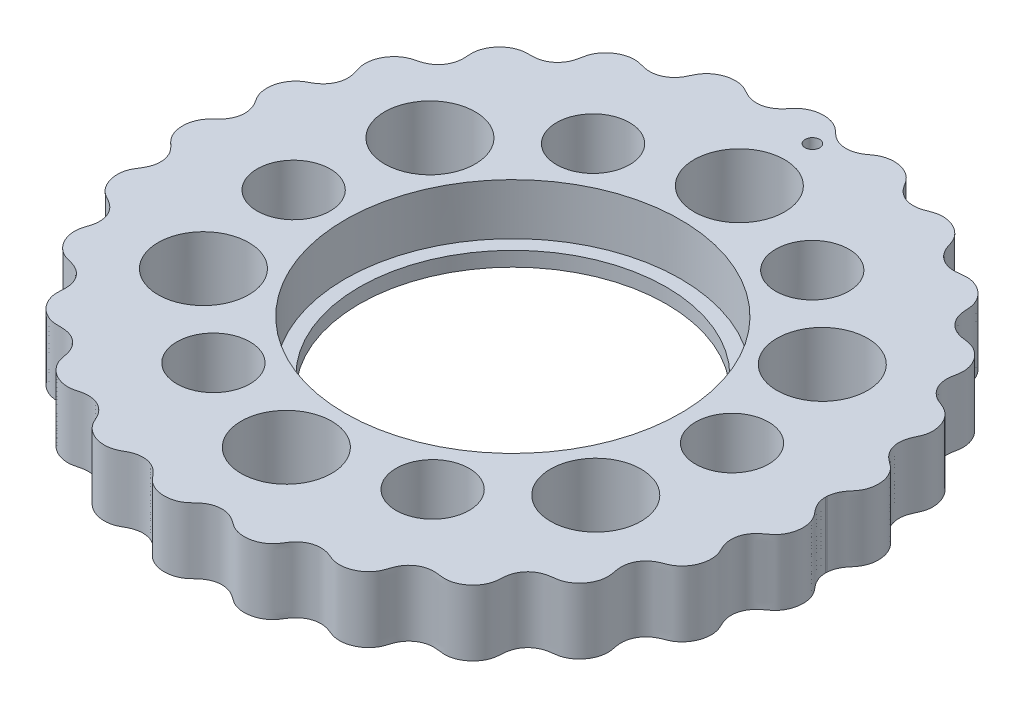
SolidWorks part; units mm, degrees
material "Like ABS"
ref_plane "Front Plane" through (0, 0, 0) normal (0, 0, 1) x (1, 0, 0)
ref_plane "Top Plane" through (0, 0, 0) normal (0, 1, 0) x (1, 0, 0)
ref_plane "Right Plane" through (0, 0, 0) normal (1, 0, 0) x (0, 0, -1)
sketch "Sketch1" plane through (0, 0, 0) normal (0, 1, 0) x (1, 0, 0)
  spline S0 degree 4 poles (18.6418, 10.5579) (18.7303, 10.3073) (18.9166, 10.0009) (19.2494, 9.7061) (19.7196, 9.4909) (20.0347, 9.3822) (20.3607, 9.2005) (20.6669, 8.9259) (20.9237, 8.5637) (21.1025, 8.1229) (21.1716, 7.6934) (21.1505, 7.3003) (21.0688, 6.9931) (20.9708, 6.7724) (20.8656, 6.5558) (20.7571, 6.3016) (20.668, 5.9591) (20.6615, 5.5306) (20.7798, 5.0848) (20.995, 4.7201) (21.2612, 4.4411) (21.5433, 4.2347) (21.8022, 4.0525) (22.045, 3.7986) (22.2501, 3.4744) (22.3932, 3.088) (22.4554, 2.6541) (22.4292, 2.264) (22.3433, 1.9326) (22.2197, 1.6594) (22.0797, 1.4428) (21.916, 1.2513) (21.7597, 1.0607) (21.6432, 0.8829) (21.5614, 0.7256) (21.5052, 0.5887) (21.4677, 0.4773) (21.4407, 0.371) (21.4222, 0.2789) (21.4076, 0.1762) (21.3996, 0.0464) (21.3987, -0.0271) (21.4069, -0.1732) (21.4219, -0.2777) (21.4443, -0.389) (21.474, -0.4968) (21.5197, -0.6294) (21.5968, -0.8019) (21.7184, -1.008) (21.898, -1.2319) (22.1006, -1.4645) (22.2832, -1.769) (22.4134, -2.1479) (22.4617, -2.5888) (22.4015, -3.0697) (22.2467, -3.4857) (22.0281, -3.8227) (21.7701, -4.0798) (21.5014, -4.2617) (21.2219, -4.4765) (20.9658, -4.7612) (20.7673, -5.1214) (20.6622, -5.5479) (20.6698, -5.9517) (20.758, -6.3091) (20.8905, -6.614) (21.0265, -6.8799) (21.1366, -7.2172) (21.1778, -7.6258) (21.1184, -8.0782) (20.9356, -8.544) (20.6762, -8.9143) (20.3782, -9.1865) (20.0975, -9.3492) (19.8699, -9.4384) (19.6428, -9.5272) (19.3961, -9.6431) (19.1116, -9.8349) (18.832, -10.1379) (18.628, -10.5267) (18.5387, -10.9199) (18.5379, -11.2864) (18.592, -11.6131) (18.6566, -11.9035) (18.677, -12.2563) (18.6137, -12.6603) (18.4454, -13.0751) (18.1627, -13.4684) (17.8328, -13.7578) (17.5261, -13.9295) (17.2611, -14.0207) (17.0556, -14.0631) (16.8894, -14.0847) (16.6814, -14.109) (16.4045, -14.1586) (16.0694, -14.2753) (15.709, -14.5087) (15.4048, -14.8538) (15.22, -15.2365) (15.1451, -15.5766) (15.1235, -15.8472) (15.1117, -16.0828) (15.086, -16.318) (15.0048, -16.6177) (14.8327, -16.9608) (14.5728, -17.2882) (14.2228, -17.573) (13.8443, -17.7633) (13.4619, -17.8627) (13.1375, -17.8769) (12.8864, -17.8466) (12.6365, -17.8129) (12.3547, -17.7936) (11.9999, -17.826) (11.5933, -17.9665) (11.2155, -18.2286) (10.9449, -18.555) (10.7906, -18.8655) (10.7038, -19.1216) (10.6339, -19.346) (10.5494, -19.5661) (10.3954, -19.8343) (10.1432, -20.1216) (9.8068, -20.3748) (9.389, -20.5646) (8.9692, -20.6515) (8.5724, -20.6465) (8.2199, -20.567) (7.923, -20.4379) (7.5842, -20.3142) (7.1893, -20.2495) (6.7562, -20.2849) (6.3193, -20.4504) (5.9761, -20.7038) (5.7522, -20.9667) (5.6061, -21.1928) (5.4827, -21.3919) (5.3455, -21.5826) (5.1293, -21.8019) (4.8139, -22.0153) (4.4253, -22.1753) (3.9731, -22.254) (3.5443, -22.2322) (3.1598, -22.1268) (2.8746, -21.9781) (2.6779, -21.8341) (2.4816, -21.6903) (2.2448, -21.5396) (1.9136, -21.3968) (1.4802, -21.3269) (1.0089, -21.3849) (0.6139, -21.5536) (0.3043, -21.7789) (0.0638, -22.0167) (-0.1578, -22.2142) (-0.448, -22.3889) (-0.804, -22.5195) (-1.2236, -22.5798) (-1.6888, -22.543) (-2.103, -22.4123) (-2.4495, -22.2124) (-2.7192, -21.9674) (-2.917, -21.7081) (-3.1594, -21.4371) (-3.4804, -21.1931) (-3.8955, -21.0162) (-4.3266, -20.9688) (-4.6986, -21.0199) (-5.0064, -21.124) (-5.2473, -21.2408) (-5.4821, -21.381) (-5.7377, -21.4982) (-6.0485, -21.5812) (-6.4098, -21.6099) (-6.8181, -21.5611) (-7.2514, -21.4098) (-7.6166, -21.1808) (-7.9026, -20.8985) (-8.1015, -20.5918) (-8.2285, -20.29) (-8.3985, -19.9669) (-8.652, -19.6514) (-9.0131, -19.3798) (-9.4202, -19.2304) (-9.7928, -19.1908) (-10.1152, -19.2172) (-10.3762, -19.2717) (-10.6376, -19.3487) (-10.9137, -19.3967) (-11.2341, -19.3981) (-11.5896, -19.3347) (-11.9717, -19.185) (-12.3532, -18.9296) (-12.6493, -18.6154) (-12.8557, -18.2686) (-12.9701, -17.92) (-13.0178, -17.5947) (-13.1323, -17.1226) (-13.3987, -16.6511) (-13.8075, -16.3174) (-14.2713, -16.1489) (-14.5895, -16.0966) (-14.8545, -16.0861) (-15.1259, -16.0953) (-15.4042, -16.0714) (-15.7134, -15.9919) (-16.04, -15.8412) (-16.3715, -15.6006) (-16.6766, -15.2574) (-16.8844, -14.8781) (-16.9969, -14.4887) (-17.0187, -14.1212) (-16.9833, -13.793) (-16.9797, -13.3053) (-17.125, -12.7827) (-17.4421, -12.3604) (-17.8514, -12.0856) (-18.1462, -11.9584) (-18.3995, -11.8839) (-18.6637, -11.8253) (-18.9258, -11.7315) (-19.2037, -11.5768) (-19.4806, -11.3493) (-19.7404, -11.0335) (-19.9495, -10.6246) (-20.0552, -10.2044) (-20.0656, -9.7977) (-19.9928, -9.4353) (-19.8758, -9.1255) (-19.784, -8.7675) (-19.7615, -8.359) (-19.8515, -7.9142) (-20.0565, -7.5324) (-20.3067, -7.2568) (-20.5604, -7.063) (-20.7872, -6.9295) (-21.0274, -6.8071) (-21.2562, -6.6501) (-21.4849, -6.4308) (-21.6945, -6.1418) (-21.8663, -5.7714) (-21.9656, -5.3231) (-21.9623, -4.8888) (-21.8783, -4.5321) (-21.7613, -4.2706) (-21.6335, -4.0565) (-21.4949, -3.8496) (-21.3375, -3.5602) (-21.217, -3.1677) (-21.1974, -2.7137) (-21.3049, -2.294) (-21.4811, -1.967) (-21.6794, -1.7187) (-21.866, -1.5347) (-22.0671, -1.3567) (-22.2478, -1.1472) (-22.4129, -0.878) (-22.5421, -0.5466) (-22.6173, -0.1335) (-22.5959, 0.3506) (-22.4661, 0.7918) (-22.2676, 1.1298) (-22.0677, 1.351) (-21.9165, 1.4911) (-21.796, 1.6037) (-21.6524, 1.752) (-21.4809, 1.9683) (-21.3145, 2.273) (-21.2055, 2.6829) (-21.2106, 3.1412) (-21.3262, 3.5408) (-21.5033, 3.8665) (-21.6848, 4.132) (-21.8148, 4.3747) (-21.9183, 4.6798) (-21.9709, 5.0457) (-21.9452, 5.4724) (-21.8071, 5.9373) (-21.6001, 6.2936) (-21.3746, 6.5445) (-21.1778, 6.703) (-21.036, 6.7965) (-20.8505, 6.8989) (-20.6264, 7.0191) (-20.3573, 7.2062) (-20.0813, 7.4975) (-19.8657, 7.8826) (-19.7711, 8.2901) (-19.7742, 8.6526) (-19.8318, 8.9622) (-19.9084, 9.2105) (-19.997, 9.4621) (-20.0507, 9.7317) (-20.0625, 10.045) (-20.0135, 10.3947) (-19.8723, 10.8081) (-19.6342, 11.1845) (-19.3432, 11.4777) (-19.047, 11.6699) (-18.8186, 11.7726) (-18.6046, 11.837) (-18.4132, 11.8827) (-18.176, 11.9484) (-17.9009, 12.0583) (-17.5928, 12.2516) (-17.2948, 12.562) (-17.0941, 12.9283) (-16.9937, 13.3178) (-16.9784, 13.6461) (-16.9965, 13.9004) (-17.0099, 14.1124) (-17.0076, 14.2827) (-16.9801, 14.5346) (-16.8899, 14.8605) (-16.7006, 15.227) (-16.3828, 15.5933) (-16.0373, 15.8442) (-15.7016, 15.9965) (-15.3896, 16.0736) (-15.1158, 16.0951) (-14.853, 16.0862) (-14.6003, 16.0964) (-14.3036, 16.1425) (-13.974, 16.253) (-13.6275, 16.4656) (-13.3337, 16.7849) (-13.1429, 17.1373) (-13.0488, 17.4509) (-13.004, 17.701) (-12.9637, 17.9088) (-12.9184, 18.0723) (-12.8283, 18.3082) (-12.6592, 18.5997) (-12.3841, 18.9062) (-11.9844, 19.1809) (-11.5862, 19.337) (-11.2216, 19.3996) (-10.8991, 19.395) (-10.6279, 19.3458) (-10.3747, 19.2715) (-10.1261, 19.2197) (-9.8257, 19.1924) (-9.4819, 19.2201) (-9.1008, 19.3403) (-8.7453, 19.5715) (-8.5077, 19.8241) (-8.3555, 20.0541) (-8.2592, 20.2364) (-8.1895, 20.3857) (-8.1029, 20.5726) (-7.9541, 20.8305) (-7.6939, 21.1232) (-7.3144, 21.3824) (-6.8604, 21.552) (-6.4441, 21.6079) (-6.0886, 21.5869) (-5.7814, 21.5126) (-5.5263, 21.405) (-5.2947, 21.2684) (-5.0616, 21.148) (-4.7636, 21.0366) (-4.3978, 20.9708) (-3.9655, 20.9994) (-3.5402, 21.1591) (-3.2052, 21.3959) (-2.9502, 21.6648) (-2.751, 21.9305) (-2.4845, 22.188) (-2.1352, 22.3988) (-1.7235, 22.5359) (-1.2663, 22.5795) (-0.8609, 22.5303) (-0.521, 22.4197) (-0.2417, 22.2695) (-0.0217, 22.0998) (0.1689, 21.9089) (0.3665, 21.7346) (0.6298, 21.5534) (0.9699, 21.4013) (1.3965, 21.3254) (1.8471, 21.3784) (2.228, 21.5266) (2.5394, 21.7249) (2.7977, 21.9316) (3.1198, 22.112) (3.5095, 22.2272) (3.9417, 22.2561) (4.3951, 22.1834) (4.7758, 22.0335) (5.0778, 21.8398) (5.3108, 21.6229) (5.4807, 21.402) (5.6181, 21.1687) (5.7678, 20.9505) (5.9804, 20.7099) (6.2746, 20.48) (6.6707, 20.304) (7.1201, 20.2475) (7.5241, 20.2991) (7.8729, 20.4154) (8.1735, 20.5505) (8.5298, 20.6425) (8.9343, 20.6554) (9.3591, 20.5746) (9.7795, 20.3902) (10.1108, 20.1489) (10.3549, 19.8842) (10.5259, 19.6143) (10.6343, 19.3565) (10.7093, 19.0953) (10.8019, 18.8462) (10.9504, 18.56) (11.1813, 18.2656) (11.5237, 17.9996) (11.9459, 17.8372) (12.3489, 17.79) (12.714, 17.818) (13.0377, 17.8733) (13.4043, 17.8713) (13.7973, 17.782) (14.1873, 17.5971) (14.5479, 17.3131) (14.8082, 16.9955) (14.9781, 16.6765) (15.0754, 16.3708) (15.1147, 16.0931) (15.1222, 15.8204) (15.1514, 15.5551) (15.2266, 15.2401) (15.3804, 14.8981) (15.6491, 14.5578) (16.0195, 14.2993) (16.3978, 14.1566) (16.7573, 14.0954) (17.0833, 14.0678) (17.4359, 13.9728) (17.7921, 13.7879) (18.1254, 13.5086) (18.4066, 13.1362) (18.5812, 12.7505) (18.6626, 12.3813) (18.6719, 12.0437) (18.6253, 11.7512) (18.553, 11.4218) (18.5268, 11.0409) (18.5933, 10.6174) (18.7938, 10.187) (19.0832, 9.8565) (19.4148, 9.6275) (19.7472, 9.4814) (20.0546, 9.3732) (20.3702, 9.1921) (20.6668, 8.9244) (20.9186, 8.5707) (21.0971, 8.1395) (21.1691, 7.7215) (21.1544, 7.3422) (21.0774, 7.012) (20.9574, 6.7402) (20.8057, 6.4375) (20.6875, 6.0727) (20.6502, 5.6447) (20.7419, 5.1786) (20.9432, 4.789) (21.2087, 4.4878) (21.4945, 4.2662) (21.7638, 4.0849) (22.0217, 3.8303) (22.2402, 3.4976) (22.393, 3.0964) (22.4576, 2.642) (22.4251, 2.2228) (22.319, 1.8567) (22.1767, 1.5831) (22.0373, 1.3938) (21.9111, 1.2447) (21.8119, 1.1238) (21.7086, 0.9838) (21.6226, 0.8451) (21.554, 0.7089) (21.5012, 0.5778) (21.4659, 0.4699) (21.4414, 0.3743) (21.425, 0.2922) (21.4143, 0.2199) (21.4075, 0.1593) (21.4009, 0.0789) (21.3996, 0.0181) (21.401, -0.0985) (21.4127, -0.2199) (21.4351, -0.355) (21.4779, -0.5212) (21.5509, -0.7067) (21.6442, -0.8848) (21.7553, -1.0512) (21.8797, -1.2084) (22.0099, -1.36) (22.1473, -1.5412) (22.273, -1.7627) (22.3996, -2.0988) (22.4619, -2.5279) (22.421, -3.0065) (22.26, -3.4597) (22.0444, -3.8016) (21.8211, -4.0307) (21.6332, -4.1724) (21.4416, -4.3083) (21.2215, -4.4808) (20.9709, -4.7472) (20.7583, -5.1317) (20.6554, -5.5913) (20.6785, -6.0142) (20.781, -6.3763) (20.9276, -6.6843) (21.0612, -6.963) (21.1479, -7.2947) (21.1712, -7.6682) (21.1116, -8.0834) (20.9479, -8.5165) (20.7051, -8.8812) (20.4074, -9.1649) (20.1242, -9.3365) (19.8924, -9.4302) (19.6596, -9.5199) (19.387, -9.6456) (19.0617, -9.8691) (18.834, -10.1425) (18.7105, -10.38) (18.6618, -10.5041) knots 0 0 0 0 0 0.005903 0.00775 0.009596 0.011443 0.013289 0.015968 0.018648 0.021201 0.023754 0.025536 0.027318 0.028209 0.0291 0.030883 0.033442 0.036001 0.038491 0.040982 0.042735 0.044487 0.04624 0.047993 0.05047 0.052947 0.055301 0.057654 0.059079 0.060504 0.061928 0.063353 0.064664 0.065974 0.066629 0.067284 0.067939 0.068594 0.069018 0.069442 0.07029 0.070911 0.071532 0.072154 0.072775 0.073396 0.074017 0.07526 0.076968 0.078675 0.080383 0.082091 0.084795 0.087498 0.090125 0.092752 0.094549 0.096347 0.098144 0.099942 0.102358 0.104774 0.107172 0.10957 0.111226 0.112881 0.114537 0.116192 0.119053 0.121914 0.124551 0.127187 0.128992 0.130797 0.1317 0.132602 0.134407 0.136832 0.139257 0.141646 0.144036 0.145684 0.147333 0.148982 0.15063 0.15348 0.156329 0.158805 0.161281 0.16314 0.164069 0.164999 0.165928 0.166858 0.168717 0.171229 0.173741 0.176268 0.178796 0.180542 0.181414 0.182287 0.184033 0.185778 0.188262 0.190745 0.19323 0.195716 0.197582 0.199449 0.200382 0.201316 0.203182 0.205703 0.208224 0.210741 0.213258 0.214997 0.215867 0.216736 0.218475 0.220214 0.222688 0.225161 0.22774 0.230318 0.232111 0.233904 0.235697 0.237491 0.240099 0.242708 0.245214 0.24772 0.249453 0.250319 0.251185 0.252918 0.25465 0.257114 0.259577 0.262166 0.264755 0.266555 0.268355 0.269255 0.270155 0.271956 0.274573 0.277191 0.279769 0.282346 0.283988 0.285631 0.287273 0.288916 0.291455 0.293994 0.296593 0.299192 0.300999 0.302806 0.304614 0.306421 0.309048 0.311675 0.314492 0.315901 0.317309 0.318863 0.320416 0.32197 0.323523 0.325967 0.32841 0.331019 0.333628 0.335442 0.337257 0.339071 0.340886 0.343522 0.346158 0.348962 0.350365 0.351767 0.353315 0.354863 0.356411 0.357959 0.360393 0.362826 0.365445 0.368064 0.369886 0.371707 0.373529 0.37535 0.380641 0.383432 0.384828 0.386224 0.387767 0.389309 0.390852 0.392395 0.394819 0.397243 0.399871 0.4025 0.404329 0.406157 0.407986 0.409814 0.415123 0.417902 0.419291 0.42068 0.422218 0.423755 0.425293 0.42683 0.429244 0.431659 0.434298 0.436936 0.438772 0.440607 0.442443 0.444278 0.446942 0.449606 0.452371 0.453754 0.455136 0.456668 0.458201 0.459733 0.461265 0.46367 0.466075 0.468724 0.471372 0.473215 0.474136 0.475057 0.476899 0.478742 0.481415 0.484087 0.486839 0.488215 0.489591 0.491119 0.492646 0.494173 0.4957 0.498096 0.500491 0.503422 0.506353 0.508183 0.509098 0.510013 0.510928 0.511843 0.513673 0.51612 0.518568 0.521142 0.523716 0.525237 0.526758 0.52828 0.529801 0.532354 0.534907 0.537685 0.540462 0.541402 0.542343 0.543283 0.544223 0.546104 0.547984 0.550517 0.553049 0.555775 0.557137 0.5585 0.560017 0.561535 0.563052 0.56457 0.566946 0.569323 0.572675 0.574351 0.576028 0.577119 0.578211 0.579302 0.580394 0.582577 0.58476 0.5873 0.589839 0.591724 0.593609 0.594552 0.595495 0.596437 0.59738 0.600165 0.60295 0.605495 0.608041 0.609559 0.611076 0.612594 0.614112 0.615394 0.616676 0.619241 0.621771 0.6243 0.626179 0.628058 0.628997 0.629937 0.630876 0.631815 0.63459 0.637365 0.639921 0.642477 0.643999 0.645522 0.647045 0.648567 0.649856 0.651144 0.653721 0.656167 0.658613 0.660441 0.661355 0.662269 0.663183 0.664097 0.665925 0.668853 0.671781 0.674179 0.676577 0.678106 0.679634 0.681163 0.682691 0.684069 0.685447 0.688203 0.690873 0.693543 0.695384 0.697224 0.699065 0.700905 0.703551 0.706197 0.708605 0.711012 0.712546 0.714079 0.715613 0.717147 0.718531 0.719916 0.722685 0.725346 0.728007 0.72984 0.731674 0.733508 0.735341 0.737977 0.740613 0.74303 0.745447 0.746986 0.748525 0.750064 0.751603 0.752994 0.754385 0.757167 0.759819 0.762471 0.764297 0.766124 0.767951 0.769777 0.772403 0.77503 0.777456 0.779883 0.781427 0.782971 0.784515 0.786059 0.787457 0.788854 0.79165 0.794292 0.796935 0.798755 0.800574 0.802394 0.804213 0.80683 0.809446 0.811882 0.814318 0.815868 0.817417 0.818967 0.820516 0.82192 0.823324 0.826132 0.828766 0.8314 0.833212 0.835025 0.836837 0.83865 0.841256 0.843862 0.846393 0.848925 0.850563 0.852201 0.85384 0.855478 0.858047 0.860616 0.86324 0.865865 0.86767 0.869476 0.871281 0.873086 0.875682 0.878279 0.88082 0.883362 0.885006 0.88665 0.888295 0.889939 0.892519 0.8951 0.897715 0.90033 0.902128 0.903927 0.905725 0.907523 0.910109 0.912695 0.915161 0.917628 0.919362 0.921096 0.921963 0.92283 0.923698 0.924565 0.925819 0.926447 0.927074 0.927701 0.928329 0.928642 0.928956 0.929269 0.929583 0.930436 0.930863 0.93129 0.932399 0.933509 0.934619 0.935729 0.936839 0.937948 0.939058 0.940168 0.941873 0.943578 0.946988 0.949698 0.952408 0.954146 0.955884 0.956753 0.957622 0.95936 0.962081 0.964802 0.967235 0.969667 0.971378 0.973089 0.9748 0.976511 0.978929 0.981347 0.984027 0.986707 0.988553 0.990399 0.991323 0.992246 0.994092 0.997046 1 1 1 1 1 construction
  spline S1 degree 4 poles (21.4, 0) (21.4, -0.0241) (21.4013, -0.0728) (21.4069, -0.1732) (21.4219, -0.2777) (21.4443, -0.389) (21.474, -0.4968) (21.5197, -0.6294) (21.5968, -0.8019) (21.7184, -1.008) (21.898, -1.2319) (22.1006, -1.4645) (22.2832, -1.769) (22.4134, -2.1479) (22.4617, -2.5888) (22.4015, -3.0697) (22.2467, -3.4857) (22.0281, -3.8227) (21.7701, -4.0798) (21.5014, -4.2617) (21.2219, -4.4765) (20.9658, -4.7612) (20.7673, -5.1214) (20.6622, -5.5479) (20.6698, -5.9517) (20.758, -6.3091) (20.8905, -6.614) (21.0265, -6.8799) (21.1366, -7.2172) (21.1778, -7.6258) (21.1184, -8.0782) (20.9356, -8.544) (20.6762, -8.9143) (20.3782, -9.1865) (20.0975, -9.3492) (19.8699, -9.4384) (19.6428, -9.5272) (19.3961, -9.6431) (19.1116, -9.8349) (18.832, -10.1379) (18.628, -10.5267) (18.5387, -10.9199) (18.5379, -11.2864) (18.592, -11.6131) (18.6566, -11.9035) (18.677, -12.2563) (18.6137, -12.6603) (18.4454, -13.0751) (18.1627, -13.4684) (17.8328, -13.7578) (17.5261, -13.9295) (17.2611, -14.0207) (17.0556, -14.0631) (16.8894, -14.0847) (16.6814, -14.109) (16.4045, -14.1586) (16.0694, -14.2753) (15.709, -14.5087) (15.4048, -14.8538) (15.22, -15.2365) (15.1451, -15.5766) (15.1235, -15.8472) (15.1117, -16.0828) (15.086, -16.318) (15.0048, -16.6177) (14.8327, -16.9608) (14.5728, -17.2882) (14.2228, -17.573) (13.8443, -17.7633) (13.4619, -17.8627) (13.1375, -17.8769) (12.8864, -17.8466) (12.6365, -17.8129) (12.3547, -17.7936) (11.9999, -17.826) (11.5933, -17.9665) (11.2155, -18.2286) (10.9449, -18.555) (10.7906, -18.8655) (10.7038, -19.1216) (10.6339, -19.346) (10.5494, -19.5661) (10.3954, -19.8343) (10.1432, -20.1216) (9.8068, -20.3748) (9.389, -20.5646) (8.9692, -20.6515) (8.5724, -20.6465) (8.2199, -20.567) (7.923, -20.4379) (7.5842, -20.3142) (7.1893, -20.2495) (6.7562, -20.2849) (6.3193, -20.4504) (5.9761, -20.7038) (5.7522, -20.9667) (5.6061, -21.1928) (5.4827, -21.3919) (5.3455, -21.5826) (5.1293, -21.8019) (4.8139, -22.0153) (4.4253, -22.1753) (3.9731, -22.254) (3.5443, -22.2322) (3.1598, -22.1268) (2.8746, -21.9781) (2.6779, -21.8341) (2.4816, -21.6903) (2.2448, -21.5396) (1.9136, -21.3968) (1.4802, -21.3269) (1.0089, -21.3849) (0.6139, -21.5536) (0.3043, -21.7789) (0.0638, -22.0167) (-0.1578, -22.2142) (-0.448, -22.3889) (-0.804, -22.5195) (-1.2236, -22.5798) (-1.6888, -22.543) (-2.103, -22.4123) (-2.4495, -22.2124) (-2.7192, -21.9674) (-2.917, -21.7081) (-3.1594, -21.4371) (-3.4804, -21.1931) (-3.8955, -21.0162) (-4.3266, -20.9688) (-4.6986, -21.0199) (-5.0064, -21.124) (-5.2473, -21.2408) (-5.4821, -21.381) (-5.7377, -21.4982) (-6.0485, -21.5812) (-6.4098, -21.6099) (-6.8181, -21.5611) (-7.2514, -21.4098) (-7.6166, -21.1808) (-7.9026, -20.8985) (-8.1015, -20.5918) (-8.2285, -20.29) (-8.3985, -19.9669) (-8.652, -19.6514) (-9.0131, -19.3798) (-9.4202, -19.2304) (-9.7928, -19.1908) (-10.1152, -19.2172) (-10.3762, -19.2717) (-10.6376, -19.3487) (-10.9137, -19.3967) (-11.2341, -19.3981) (-11.5896, -19.3347) (-11.9717, -19.185) (-12.3532, -18.9296) (-12.6493, -18.6154) (-12.8557, -18.2686) (-12.9701, -17.92) (-13.0178, -17.5947) (-13.1323, -17.1226) (-13.3987, -16.6511) (-13.8075, -16.3174) (-14.2713, -16.1489) (-14.5895, -16.0966) (-14.8545, -16.0861) (-15.1259, -16.0953) (-15.4042, -16.0714) (-15.7134, -15.9919) (-16.04, -15.8412) (-16.3715, -15.6006) (-16.6766, -15.2574) (-16.8844, -14.8781) (-16.9969, -14.4887) (-17.0187, -14.1212) (-16.9833, -13.793) (-16.9797, -13.3053) (-17.125, -12.7827) (-17.4421, -12.3604) (-17.8514, -12.0856) (-18.1462, -11.9584) (-18.3995, -11.8839) (-18.6637, -11.8253) (-18.9258, -11.7315) (-19.2037, -11.5768) (-19.4806, -11.3493) (-19.7404, -11.0335) (-19.9495, -10.6246) (-20.0552, -10.2044) (-20.0656, -9.7977) (-19.9928, -9.4353) (-19.8758, -9.1255) (-19.784, -8.7675) (-19.7615, -8.359) (-19.8515, -7.9142) (-20.0565, -7.5324) (-20.3067, -7.2568) (-20.5604, -7.063) (-20.7872, -6.9295) (-21.0274, -6.8071) (-21.2562, -6.6501) (-21.4849, -6.4308) (-21.6945, -6.1418) (-21.8663, -5.7714) (-21.9656, -5.3231) (-21.9623, -4.8888) (-21.8783, -4.5321) (-21.7613, -4.2706) (-21.6335, -4.0565) (-21.4949, -3.8496) (-21.3375, -3.5602) (-21.217, -3.1677) (-21.1974, -2.7137) (-21.3049, -2.294) (-21.4811, -1.967) (-21.6794, -1.7187) (-21.866, -1.5347) (-22.0671, -1.3567) (-22.2478, -1.1472) (-22.4129, -0.878) (-22.5421, -0.5466) (-22.6173, -0.1335) (-22.5959, 0.3506) (-22.4661, 0.7918) (-22.2676, 1.1298) (-22.0677, 1.351) (-21.9165, 1.4911) (-21.796, 1.6037) (-21.6524, 1.752) (-21.4809, 1.9683) (-21.3145, 2.273) (-21.2055, 2.6829) (-21.2106, 3.1412) (-21.3262, 3.5408) (-21.5033, 3.8665) (-21.6848, 4.132) (-21.8148, 4.3747) (-21.9183, 4.6798) (-21.9709, 5.0457) (-21.9452, 5.4724) (-21.8071, 5.9373) (-21.6001, 6.2936) (-21.3746, 6.5445) (-21.1778, 6.703) (-21.036, 6.7965) (-20.8505, 6.8989) (-20.6264, 7.0191) (-20.3573, 7.2062) (-20.0813, 7.4975) (-19.8657, 7.8826) (-19.7711, 8.2901) (-19.7742, 8.6526) (-19.8318, 8.9622) (-19.9084, 9.2105) (-19.997, 9.4621) (-20.0507, 9.7317) (-20.0625, 10.045) (-20.0135, 10.3947) (-19.8723, 10.8081) (-19.6342, 11.1845) (-19.3432, 11.4777) (-19.047, 11.6699) (-18.8186, 11.7726) (-18.6046, 11.837) (-18.4132, 11.8827) (-18.176, 11.9484) (-17.9009, 12.0583) (-17.5928, 12.2516) (-17.2948, 12.562) (-17.0941, 12.9283) (-16.9937, 13.3178) (-16.9784, 13.6461) (-16.9965, 13.9004) (-17.0099, 14.1124) (-17.0076, 14.2827) (-16.9801, 14.5346) (-16.8899, 14.8605) (-16.7006, 15.227) (-16.3828, 15.5933) (-16.0373, 15.8442) (-15.7016, 15.9965) (-15.3896, 16.0736) (-15.1158, 16.0951) (-14.853, 16.0862) (-14.6003, 16.0964) (-14.3036, 16.1425) (-13.974, 16.253) (-13.6275, 16.4656) (-13.3337, 16.7849) (-13.1429, 17.1373) (-13.0488, 17.4509) (-13.004, 17.701) (-12.9637, 17.9088) (-12.9184, 18.0723) (-12.8283, 18.3082) (-12.6592, 18.5997) (-12.3841, 18.9062) (-11.9844, 19.1809) (-11.5862, 19.337) (-11.2216, 19.3996) (-10.8991, 19.395) (-10.6279, 19.3458) (-10.3747, 19.2715) (-10.1261, 19.2197) (-9.8257, 19.1924) (-9.4819, 19.2201) (-9.1008, 19.3403) (-8.7453, 19.5715) (-8.5077, 19.8241) (-8.3555, 20.0541) (-8.2592, 20.2364) (-8.1895, 20.3857) (-8.1029, 20.5726) (-7.9541, 20.8305) (-7.6939, 21.1232) (-7.3144, 21.3824) (-6.8604, 21.552) (-6.4441, 21.6079) (-6.0886, 21.5869) (-5.7814, 21.5126) (-5.5263, 21.405) (-5.2947, 21.2684) (-5.0616, 21.148) (-4.7636, 21.0366) (-4.3978, 20.9708) (-3.9655, 20.9994) (-3.5402, 21.1591) (-3.2052, 21.3959) (-2.9502, 21.6648) (-2.751, 21.9305) (-2.4845, 22.188) (-2.1352, 22.3988) (-1.7235, 22.5359) (-1.2663, 22.5795) (-0.8609, 22.5303) (-0.521, 22.4197) (-0.2417, 22.2695) (-0.0217, 22.0998) (0.1689, 21.9089) (0.3665, 21.7346) (0.6298, 21.5534) (0.9699, 21.4013) (1.3965, 21.3254) (1.8471, 21.3784) (2.228, 21.5266) (2.5394, 21.7249) (2.7977, 21.9316) (3.1198, 22.112) (3.5095, 22.2272) (3.9417, 22.2561) (4.3951, 22.1834) (4.7758, 22.0335) (5.0778, 21.8398) (5.3108, 21.6229) (5.4807, 21.402) (5.6181, 21.1687) (5.7678, 20.9505) (5.9804, 20.7099) (6.2746, 20.48) (6.6707, 20.304) (7.1201, 20.2475) (7.5241, 20.2991) (7.8729, 20.4154) (8.1735, 20.5505) (8.5298, 20.6425) (8.9343, 20.6554) (9.3591, 20.5746) (9.7795, 20.3902) (10.1108, 20.1489) (10.3549, 19.8842) (10.5259, 19.6143) (10.6343, 19.3565) (10.7093, 19.0953) (10.8019, 18.8462) (10.9504, 18.56) (11.1813, 18.2656) (11.5237, 17.9996) (11.9459, 17.8372) (12.3489, 17.79) (12.714, 17.818) (13.0377, 17.8733) (13.4043, 17.8713) (13.7973, 17.782) (14.1873, 17.5971) (14.5479, 17.3131) (14.8082, 16.9955) (14.9781, 16.6765) (15.0754, 16.3708) (15.1147, 16.0931) (15.1222, 15.8204) (15.1514, 15.5551) (15.2266, 15.2401) (15.3804, 14.8981) (15.6491, 14.5578) (16.0195, 14.2993) (16.3978, 14.1566) (16.7573, 14.0954) (17.0833, 14.0678) (17.4359, 13.9728) (17.7921, 13.7879) (18.1254, 13.5086) (18.4066, 13.1362) (18.5812, 12.7505) (18.6626, 12.3813) (18.6719, 12.0437) (18.6253, 11.7512) (18.553, 11.4218) (18.5268, 11.0409) (18.5933, 10.6174) (18.7938, 10.187) (19.0832, 9.8565) (19.4148, 9.6275) (19.7472, 9.4814) (20.0546, 9.3732) (20.3702, 9.1921) (20.6668, 8.9244) (20.9186, 8.5707) (21.0971, 8.1395) (21.1691, 7.7215) (21.1544, 7.3422) (21.0774, 7.012) (20.9574, 6.7402) (20.8057, 6.4375) (20.6875, 6.0727) (20.6502, 5.6447) (20.7419, 5.1786) (20.9432, 4.789) (21.2087, 4.4878) (21.4945, 4.2662) (21.7638, 4.0849) (22.0217, 3.8303) (22.2402, 3.4976) (22.393, 3.0964) (22.4576, 2.642) (22.4251, 2.2228) (22.319, 1.8567) (22.1767, 1.5831) (22.0373, 1.3938) (21.9111, 1.2447) (21.8119, 1.1238) (21.7086, 0.9838) (21.6226, 0.8451) (21.554, 0.7089) (21.5012, 0.5778) (21.4659, 0.4699) (21.4414, 0.3743) (21.425, 0.2922) (21.4143, 0.2199) (21.4075, 0.1593) (21.404, 0.1171) (21.4025, 0.0924) (21.4019, 0.0803) knots 0.07029 0.07029 0.07029 0.07029 0.07029 0.070911 0.071532 0.072154 0.072775 0.073396 0.074017 0.07526 0.076968 0.078675 0.080383 0.082091 0.084795 0.087498 0.090125 0.092752 0.094549 0.096347 0.098144 0.099942 0.102358 0.104774 0.107172 0.10957 0.111226 0.112881 0.114537 0.116192 0.119053 0.121914 0.124551 0.127187 0.128992 0.130797 0.1317 0.132602 0.134407 0.136832 0.139257 0.141646 0.144036 0.145684 0.147333 0.148982 0.15063 0.15348 0.156329 0.158805 0.161281 0.16314 0.164069 0.164999 0.165928 0.166858 0.168717 0.171229 0.173741 0.176268 0.178796 0.180542 0.181414 0.182287 0.184033 0.185778 0.188262 0.190745 0.19323 0.195716 0.197582 0.199449 0.200382 0.201316 0.203182 0.205703 0.208224 0.210741 0.213258 0.214997 0.215867 0.216736 0.218475 0.220214 0.222688 0.225161 0.22774 0.230318 0.232111 0.233904 0.235697 0.237491 0.240099 0.242708 0.245214 0.24772 0.249453 0.250319 0.251185 0.252918 0.25465 0.257114 0.259577 0.262166 0.264755 0.266555 0.268355 0.269255 0.270155 0.271956 0.274573 0.277191 0.279769 0.282346 0.283988 0.285631 0.287273 0.288916 0.291455 0.293994 0.296593 0.299192 0.300999 0.302806 0.304614 0.306421 0.309048 0.311675 0.314492 0.315901 0.317309 0.318863 0.320416 0.32197 0.323523 0.325967 0.32841 0.331019 0.333628 0.335442 0.337257 0.339071 0.340886 0.343522 0.346158 0.348962 0.350365 0.351767 0.353315 0.354863 0.356411 0.357959 0.360393 0.362826 0.365445 0.368064 0.369886 0.371707 0.373529 0.37535 0.380641 0.383432 0.384828 0.386224 0.387767 0.389309 0.390852 0.392395 0.394819 0.397243 0.399871 0.4025 0.404329 0.406157 0.407986 0.409814 0.415123 0.417902 0.419291 0.42068 0.422218 0.423755 0.425293 0.42683 0.429244 0.431659 0.434298 0.436936 0.438772 0.440607 0.442443 0.444278 0.446942 0.449606 0.452371 0.453754 0.455136 0.456668 0.458201 0.459733 0.461265 0.46367 0.466075 0.468724 0.471372 0.473215 0.474136 0.475057 0.476899 0.478742 0.481415 0.484087 0.486839 0.488215 0.489591 0.491119 0.492646 0.494173 0.4957 0.498096 0.500491 0.503422 0.506353 0.508183 0.509098 0.510013 0.510928 0.511843 0.513673 0.51612 0.518568 0.521142 0.523716 0.525237 0.526758 0.52828 0.529801 0.532354 0.534907 0.537685 0.540462 0.541402 0.542343 0.543283 0.544223 0.546104 0.547984 0.550517 0.553049 0.555775 0.557137 0.5585 0.560017 0.561535 0.563052 0.56457 0.566946 0.569323 0.572675 0.574351 0.576028 0.577119 0.578211 0.579302 0.580394 0.582577 0.58476 0.5873 0.589839 0.591724 0.593609 0.594552 0.595495 0.596437 0.59738 0.600165 0.60295 0.605495 0.608041 0.609559 0.611076 0.612594 0.614112 0.615394 0.616676 0.619241 0.621771 0.6243 0.626179 0.628058 0.628997 0.629937 0.630876 0.631815 0.63459 0.637365 0.639921 0.642477 0.643999 0.645522 0.647045 0.648567 0.649856 0.651144 0.653721 0.656167 0.658613 0.660441 0.661355 0.662269 0.663183 0.664097 0.665925 0.668853 0.671781 0.674179 0.676577 0.678106 0.679634 0.681163 0.682691 0.684069 0.685447 0.688203 0.690873 0.693543 0.695384 0.697224 0.699065 0.700905 0.703551 0.706197 0.708605 0.711012 0.712546 0.714079 0.715613 0.717147 0.718531 0.719916 0.722685 0.725346 0.728007 0.72984 0.731674 0.733508 0.735341 0.737977 0.740613 0.74303 0.745447 0.746986 0.748525 0.750064 0.751603 0.752994 0.754385 0.757167 0.759819 0.762471 0.764297 0.766124 0.767951 0.769777 0.772403 0.77503 0.777456 0.779883 0.781427 0.782971 0.784515 0.786059 0.787457 0.788854 0.79165 0.794292 0.796935 0.798755 0.800574 0.802394 0.804213 0.80683 0.809446 0.811882 0.814318 0.815868 0.817417 0.818967 0.820516 0.82192 0.823324 0.826132 0.828766 0.8314 0.833212 0.835025 0.836837 0.83865 0.841256 0.843862 0.846393 0.848925 0.850563 0.852201 0.85384 0.855478 0.858047 0.860616 0.86324 0.865865 0.86767 0.869476 0.871281 0.873086 0.875682 0.878279 0.88082 0.883362 0.885006 0.88665 0.888295 0.889939 0.892519 0.8951 0.897715 0.90033 0.902128 0.903927 0.905725 0.907523 0.910109 0.912695 0.915161 0.917628 0.919362 0.921096 0.921963 0.92283 0.923698 0.924565 0.925819 0.926447 0.927074 0.927701 0.928329 0.928642 0.928956 0.929269 0.929583 0.929583 0.929583 0.929583 0.929583
  spline S2 degree 1 poles (21.4019, 0.0803) (21.4, 0) knots 0 0 1 1
extrude "Boss-Extrude1" add sketch "Sketch1" along normal blind 4.5
sketch "Sketch2" plane through (0, 4.5, 0) normal (0, 1, 0) x (1, 0, 0)
  circle A0 centre (0, 0) radius 11.475
  dimension "D1" = 22.95
extrude "Cut-Extrude1" cut sketch "Sketch2" against normal up to surface (4.5 mm away) up to face at (21.401, 0, -0.0402)
sketch "Sketch3" plane through (0, 4.5, 0) normal (0, 1, 0) x (1, 0, 0)
  line L0 (0, 0) -> (0, 15.5) construction
  circle A0 centre (0, 15.5) radius 3.1
  dimension "D1" = 6.2
  dimension "D2" = 15.5
extrude "Cut-Extrude2" cut sketch "Sketch3" against normal up to surface (4.5 mm away) up to face at (0, 0, -11.475)
pattern_circular "CirPattern1" count 6 over 360 about axis through (0, 0, 0) along (0, 1, 0) of "Cut-Extrude2"
sketch "Sketch5" plane through (0, 4.5, 0) normal (0, 1, 0) x (1, 0, 0)
  line L0 (0, 15.5) -> (0, 0) construction
  line L1 (0, 0) -> (7.5, 12.9904) construction
  circle A0 centre (7.5, 12.9904) radius 2.5
  dimension "D2" = 5
  dimension "D1" = 30
  dimension "D3" = 15
extrude "Cut-Extrude3" cut sketch "Sketch5" against normal up to surface (4.5 mm away) up to face at (-13.4234, 0, -10.85)
pattern_circular "CirPattern2" count 6 over 360 about axis through (0, 0, 0) along (0, 1, 0) of "Cut-Extrude3"
sketch "Sketch6" plane through (0, 4.5, 0) normal (0, 1, 0) x (1, 0, 0)
  line L0 (0, 0) -> (0, 20.5) construction
  circle A0 centre (0, 20.5) radius 0.5
  dimension "D2" = 1
  dimension "D1" = 20.5
extrude "Cut-Extrude4" cut sketch "Sketch6" against normal up to surface (4.5 mm away) up to face at (-7.5, 0, -15.4904)
sketch "Sketch7" plane through (0, 0, 0) normal (0, -1, 0) x (1, 0, 0)
  circle A0 centre (0, 0) radius 10.5
  circle A1 centre (0, 0) radius 11.6827
  dimension "D1" = 21
extrude "Boss-Extrude2" add sketch "Sketch7" against normal blind 1
